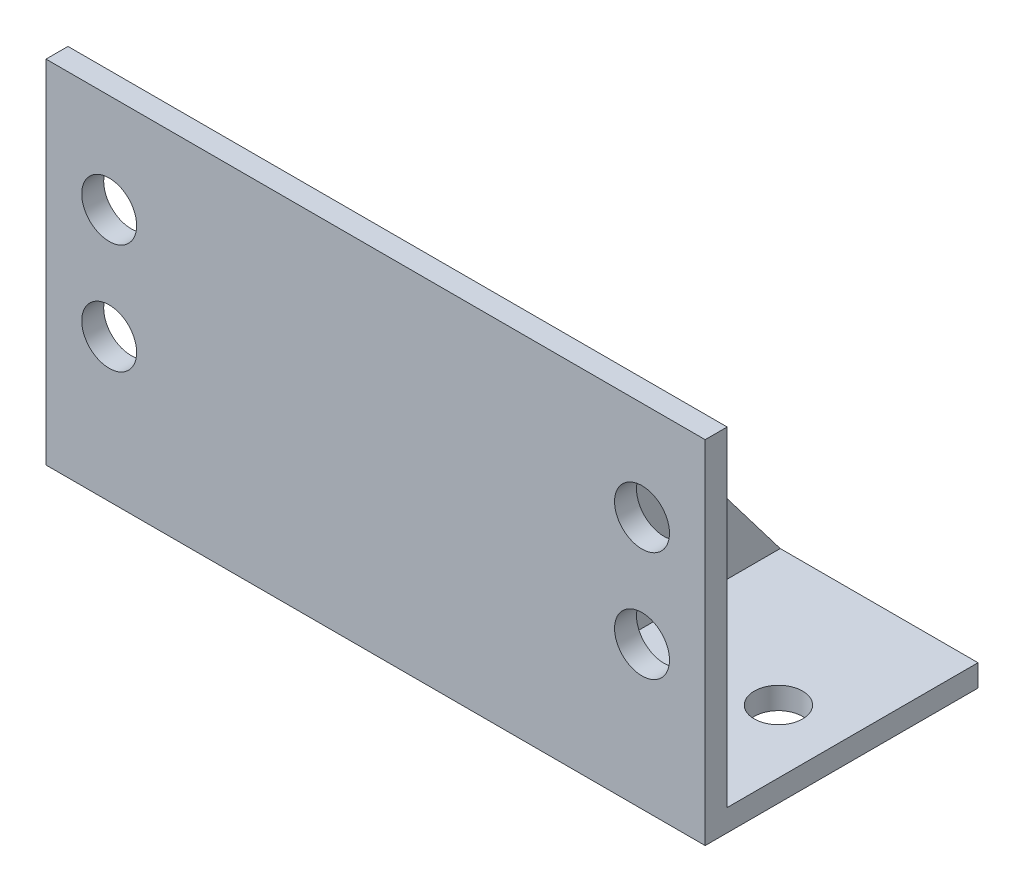
SolidWorks part; units mm, degrees
ref_plane "前视基准面" through (0, 0, 0) normal (0, 0, 1) x (1, 0, 0)
ref_plane "上视基准面" through (0, 0, 0) normal (0, 1, 0) x (1, 0, 0)
ref_plane "右视基准面" through (0, 0, 0) normal (1, 0, 0) x (0, 0, -1)
other "Configuration Table"
sketch "草圖1" plane through (0, 0, 0) normal (0, 1, 0) x (1, 0, 0)
  line L0 (-24.25, 0) -> (24.25, 0)
  line L1 (-30, 12.4165) -> (30, 12.4165)
  line L2 (-30, 12.4165) -> (-30, -12.4165)
  line L3 (-30, -12.4165) -> (30, -12.4165)
  line L4 (30, 12.4165) -> (30, -12.4165)
  line L5 (-30, 12.4165) -> (30, -12.4165) construction
  line L6 (-30, -12.4165) -> (30, 12.4165) construction
  circle A0 centre (-24.25, 0) radius 2.2
  circle A1 centre (0, 0) radius 2.2
  circle A2 centre (24.25, 0) radius 2.2
  point P0 (0, 0)
  point P9 (0, 0)
  dimension "D1" = 3
extrude "填料-伸長2" add sketch "草圖1" along normal blind 2 contours L3 L4 L1 L2 | A2 | A1 | A0
sketch "草圖6" plane through (0, 2, 0) normal (0, 1, 0) x (1, 0, 0)
  line L1 (-30, 12.4165) -> (-30, -12.4165) construction
  line L4 (-30, 12.4165) -> (30, 12.4165) construction
  line L5 (-12, 12.4165) -> (-10, 12.4165)
  line L6 (-12, 12.4165) -> (-12, -10.4165)
  line L7 (-12, -10.4165) -> (-10, -10.4165)
  line L8 (-10, 12.4165) -> (-10, -10.4165)
  line L9 (-30, -10.4165) -> (30, -10.4165)
  line L10 (10, 12.4165) -> (12, 12.4165)
  line L11 (10, 12.4165) -> (10, -10.4165)
  line L12 (10, -10.4165) -> (12, -10.4165)
  line L13 (12, 12.4165) -> (12, -10.4165)
  line L14 (-30, -10.4165) -> (-30, -12.4165)
  line L15 (-30, -12.4165) -> (30, -12.4165)
  line L16 (30, -10.4165) -> (30, -12.4165)
  point P6 (0, 0)
  point P7 (0, 0)
  dimension "D1" = 2
  dimension "D2" = 2
  dimension "D3" = 2
  dimension "D4" = 18
  dimension "D5" = 20
extrude "填料-伸長3" add sketch "草圖6" along normal blind 30 contours L11 L12 L13 L10 | L9 L16 L15 L14 | L6 L7 L8 L5
sketch "草圖8" plane through (-12, 0, 0) normal (-1, 0, 0) x (0, 0, 1)
  line L0 (10.4165, 32) -> (-12.4165, 2)
  line L1 (-12.4165, 2) -> (-12.4165, 32)
  line L2 (-12.4165, 32) -> (10.4165, 32)
extrude "除料-伸長1" cut sketch "草圖8" against normal through all contours L2 L0 L1
sketch "草圖9" plane through (0, 0, 12.4165) normal (0, 0, 1) x (1, 0, 0)
  line L0 (0, 0) -> (0, 32)
  line L1 (-30, 32) -> (30, 32) construction
  line L2 (-30, 0) -> (30, 0) construction
  circle A0 centre (-24.25, 13) radius 2.5
  circle A1 centre (24.25, 13) radius 2.5
  circle A2 centre (24.25, 23) radius 2.5
  circle A3 centre (-24.25, 23) radius 2.5
  dimension "D1" = 13
  dimension "D4" = 24.25
  dimension "D2" = 2
  dimension "D3" = 2
extrude "除料-伸長2" cut sketch "草圖9" against normal through all contours A0 | A3 | A1 | A2
